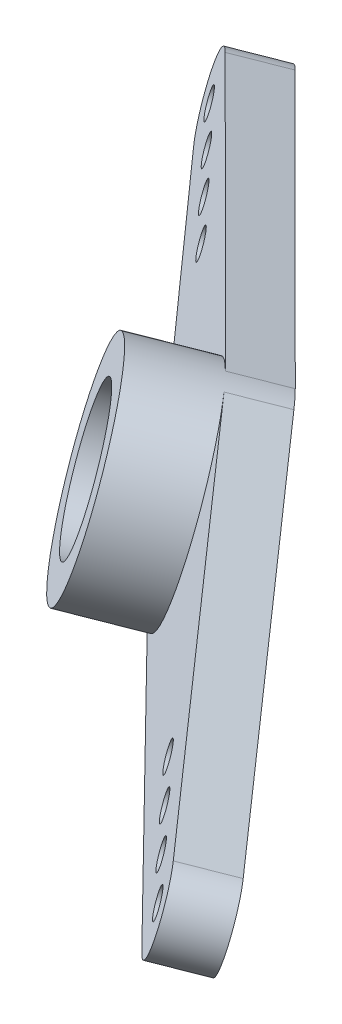
SolidWorks part; units mm, degrees
ref_plane "Front Plane" through (0, 0, 0) normal (0, 0, 1) x (1, 0, 0)
ref_plane "Top Plane" through (0, 0, 0) normal (0, 1, 0) x (1, 0, 0)
ref_plane "Right Plane" through (0, 0, 0) normal (1, 0, 0) x (0, 0, -1)
sketch "Sketch1" plane through (-26.119, 9.879, 23.9542) normal (-0.7099, 0.2685, 0.6511) x (0.6812, 0.027, 0.7316)
  line L0 (-10.1796, -104.3301) -> (4.4647, -106.2777)
  line L1 (4.3043, -107.484) -> (-10.5697, -107.2634) construction
  line L2 (4.4289, -108.6945) -> (-10.2668, -110.2069)
  line L3 (-10.5697, -107.2634) -> (-10.5697, -102.6165) construction
  line L4 (-25.4437, -107.484) -> (-10.5697, -107.2634) construction
  line L5 (-25.5683, -108.6945) -> (-10.8726, -110.2069)
  line L6 (-10.9598, -104.3301) -> (-25.6041, -106.2777)
  circle A0 centre (-10.5697, -107.2634) radius 1.134
  arc A1 (-10.1796, -104.3301) -> (-10.9598, -104.3301) centre (-10.5697, -107.2634) ccw
  arc A2 (4.4647, -106.2777) -> (4.4289, -108.6945) centre (4.3043, -107.484) cw
  circle A3 centre (4.3043, -107.484) radius 0.3998
  circle A4 centre (2.5263, -107.4576) radius 0.3998
  circle A5 centre (0.7483, -107.4312) radius 0.3998
  circle A6 centre (-1.0297, -107.4049) radius 0.3998
  circle A7 centre (-20.1097, -107.4049) radius 0.3998
  circle A8 centre (-21.8877, -107.4312) radius 0.3998
  circle A9 centre (-23.6657, -107.4576) radius 0.3998
  circle A10 centre (-25.4437, -107.484) radius 0.3998
  arc A11 (-25.6041, -106.2777) -> (-25.5683, -108.6945) centre (-25.4437, -107.484) ccw
  arc A12 (-10.8726, -110.2069) -> (-10.2668, -110.2069) centre (-10.5697, -107.2634) ccw
  dimension "D1" = 19.05
  dimension "D2" = 1.2169
  dimension "D3" = 1.778
  dimension "D4" = 1.778
  dimension "D5" = 1.778
  dimension "D6" = 2.9591
extrude "Boss-Extrude1" add sketch "Sketch1" along normal blind 1.4986
sketch "Sketch2" plane through (-27.1828, 10.2814, 24.9299) normal (-0.7099, 0.2685, 0.6511) x (0.6812, 0.027, 0.7316)
  circle A0 centre (-10.5697, -107.2634) radius 2.9591
  dimension "D1" = 5.9182
extrude "Boss-Extrude2" add sketch "Sketch2" along normal blind 2.159
sketch "Sketch3" plane through (-28.7156, 10.8611, 26.3356) normal (-0.7099, 0.2685, 0.6511) x (0.6812, 0.027, 0.7316)
  circle A0 centre (-10.5697, -107.2634) radius 1.9812
  dimension "D1" = 3.9624
extrude "Cut-Extrude1" cut sketch "Sketch3" against normal blind 2.54
sketch "Sketch4" [suppressed] plane through (-27.1828, 10.2814, 24.9299) normal (-0.7099, 0.2685, 0.6511) x (0.609, -0.2303, 0.759)
  line L2 (-22.7562, -13.6464) -> (-8.1884, -11.1913)
  line L3 (-9.8372, -5.5498) -> (-23.4342, -11.3264)
  line L4 (-22.7562, -13.6464) -> (-8.1884, -11.1913)
  line L5 (-9.8372, -5.5498) -> (-23.4342, -11.3264)
  arc A2 (-9.8372, -5.5498) -> (-8.1884, -11.1913) centre (-8.6801, -8.2733) ccw
  arc A3 (-23.4342, -11.3264) -> (-22.7562, -13.6464) centre (-22.9584, -12.4464) ccw
  arc A4 (-9.8372, -5.5498) -> (-8.1884, -11.1913) centre (-8.6801, -8.2733) ccw
  arc A5 (-23.4342, -11.3264) -> (-22.7562, -13.6464) centre (-22.9584, -12.4464) ccw
  dimension "D1" = 0
extrude "Cut-Extrude2" [suppressed] cut sketch "Sketch4" against normal through all
